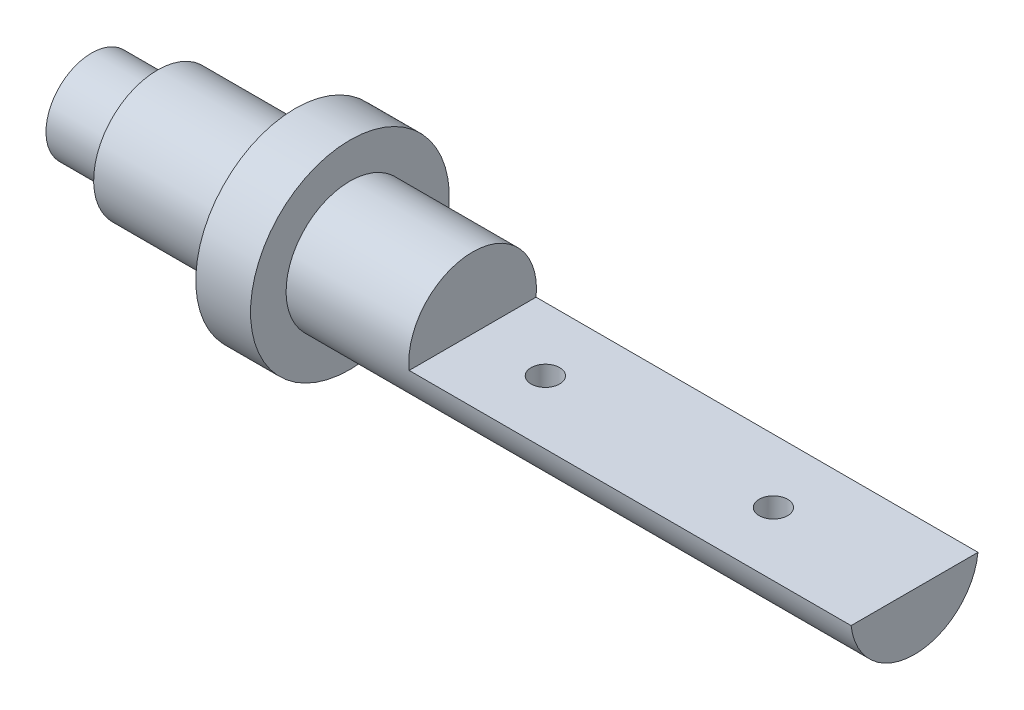
SolidWorks part; units mm, degrees
ref_plane "Front Plane" through (0, 0, 0) normal (0, 0, 1) x (1, 0, 0)
ref_plane "Top Plane" through (0, 0, 0) normal (0, 1, 0) x (1, 0, 0)
ref_plane "Right Plane" through (0, 0, 0) normal (1, 0, 0) x (0, 0, -1)
sketch "Sketch1" plane through (0, 0, 0) normal (0, 0, 1) x (1, 0, 0)
  line L0 (0, 0) -> (0, 20)
  line L1 (0, 20) -> (28.9, 20)
  line L2 (28.9, 20) -> (28.9, 28)
  line L3 (28.9, 28) -> (89.3, 28)
  line L4 (89.3, 28) -> (89.3, 43.6)
  line L5 (89.3, 43.6) -> (113.3, 43.6)
  line L6 (113.3, 43.6) -> (113.3, 28)
  line L7 (113.3, 28) -> (360.9, 28)
  line L8 (360.9, 28) -> (360.9, 0)
  line L9 (360.9, 0) -> (0, 0)
  dimension "D1" = 28.9
  dimension "D2" = 89.3
  dimension "D3" = 24
  dimension "D4" = 247.6
  dimension "D5" = 20
  dimension "D6" = 28
  dimension "D7" = 43.6
revolve "Revolve1" add sketch "Sketch1" angle 360 about L9
sketch "Sketch2" plane through (0, 0, 0) normal (0, 0, 1) x (1, 0, 0)
  line L0 (360.9, 28) -> (113.3, 28) construction
  line L1 (167.1, 28) -> (360.9, 28)
  line L2 (167.1, 28) -> (167.1, -3.1)
  line L3 (167.1, -3.1) -> (360.9, -3.1)
  line L4 (360.9, 28) -> (360.9, -3.1)
  line L6 (360.9, -28) -> (360.9, 28) construction
  dimension "D1" = 31.1
  dimension "D2" = 193.8
extrude "Cut-Extrude1" cut sketch "Sketch2" against normal through all both and the other way through all
hole_wizard "Hole1" positions "Sketch3" profile "Sketch4" legacy end condition through all
sketch "Sketch3" plane through (0, -3.1, 0) normal (0, 1, 0) x (1, 0, 0)
  line L0 (360.9, -27.8279) -> (360.9, 27.8279) construction
  point P0 (199, 0)
  point P2 (299, 0)
  dimension "D1" = 100
  dimension "D2" = 61.9
sketch "Sketch4" plane through (199, -3.1, 0) normal (1, 0, 0) x (0, 0, 1)
  line L0 (0, 0) -> (0, 40.5)
  line L1 (0, 40.5) -> (6.25, 40.5)
  line L2 (6.25, 40.5) -> (6.25, 0)
  line L3 (6.25, 0) -> (0, 0)
  line L4 (0, 110) -> (0, -10) construction
  dimension "Diameter" = 12.5
  dimension "Depth" = 40.5
